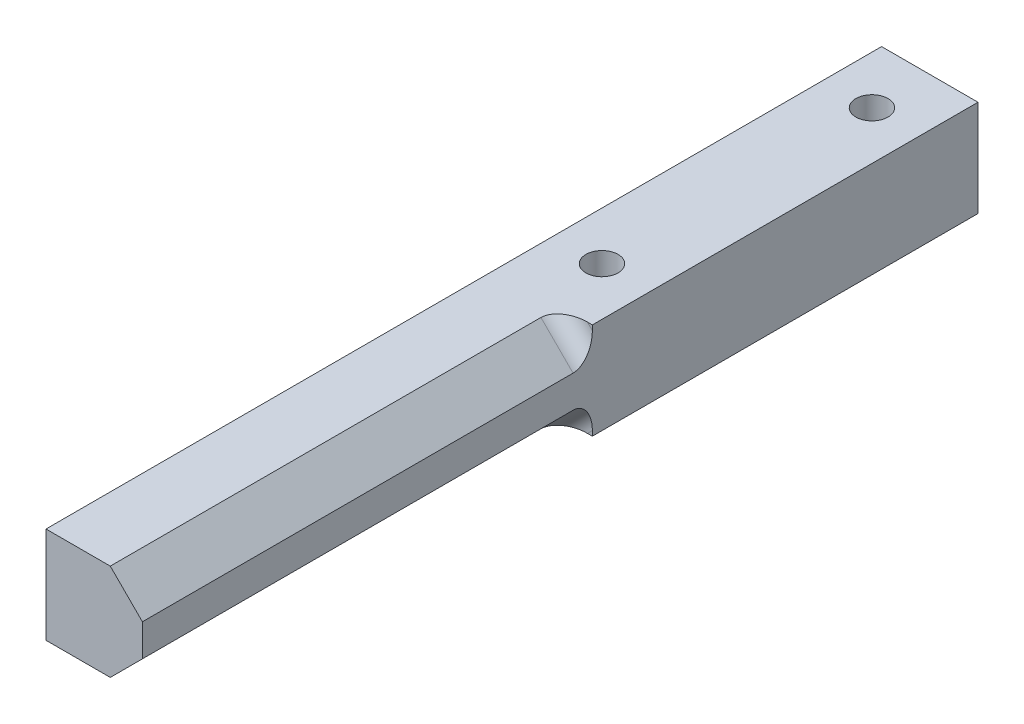
SolidWorks part; units mm, degrees
ref_plane "Plan de face" through (0, 0, 0) normal (0, 0, 1) x (1, 0, 0)
ref_plane "Plan de dessus" through (0, 0, 0) normal (0, 1, 0) x (1, 0, 0)
ref_plane "Plan de droite" through (0, 0, 0) normal (1, 0, 0) x (0, 0, -1)
sketch "Esquisse1" plane through (0, 0, 0) normal (0, 0, 1) x (1, 0, 0)
  line L1 (-3.75, -3.75) -> (3.75, -3.75)
  line L2 (-3.75, -3.75) -> (-3.75, 3.75)
  line L3 (-3.75, 3.75) -> (3.75, 3.75)
  line L4 (3.75, -3.75) -> (3.75, 3.75)
  line L5 (-3.75, -3.75) -> (3.75, 3.75) construction
  line L6 (-3.75, 3.75) -> (3.75, -3.75) construction
  point P0 (0, 0)
  dimension "D1" = 7.5
extrude "Boss.-Extru.1" add sketch "Esquisse1" along normal blind 65
sketch "Esquisse2" plane through (0, 3.75, 0) normal (0, 1, 0) x (1, 0, 0)
  line L0 (3.75, 0) -> (-3.75, 0) construction
  circle A0 centre (0, -4.5) radius 1.25
  circle A1 centre (0, -25.5) radius 1.25
  dimension "D1" = 2.5
  dimension "D3" = 21
  dimension "D2" = 4.5
extrude "Enlèv. mat.-Extru.1" cut sketch "Esquisse2" against normal through all
sketch "Esquisse3" plane through (0, 0, 0) normal (0, 0, -1) x (-1, 0, 0)
  line L0 (-1.25, 3.75) -> (-3.75, 3.75)
  line L1 (-3.75, 3.75) -> (3.75, 3.75) construction
  line L2 (-3.75, 3.75) -> (-3.75, 1.25)
  line L3 (-3.75, -3.75) -> (-3.75, 3.75) construction
  line L4 (-3.75, 1.25) -> (-3.75, -1.25) construction
  line L5 (-3.75, -1.25) -> (-3.75, -3.75)
  line L6 (-3.75, -3.75) -> (-1.25, -3.75)
  line L7 (3.75, -3.75) -> (-3.75, -3.75) construction
  line L8 (-3.75, 1.25) -> (-1.25, 3.75)
  line L9 (-1.25, -3.75) -> (-3.75, -1.25)
extrude "Enlèv. mat.-Extru.2" cut sketch "Esquisse3" against normal through all from offset 30 offset against normal yes
fillet "Congé1" radius 1.5 2 edges at (2.5, -2.5, 30) (2.5, 2.5, 30)
